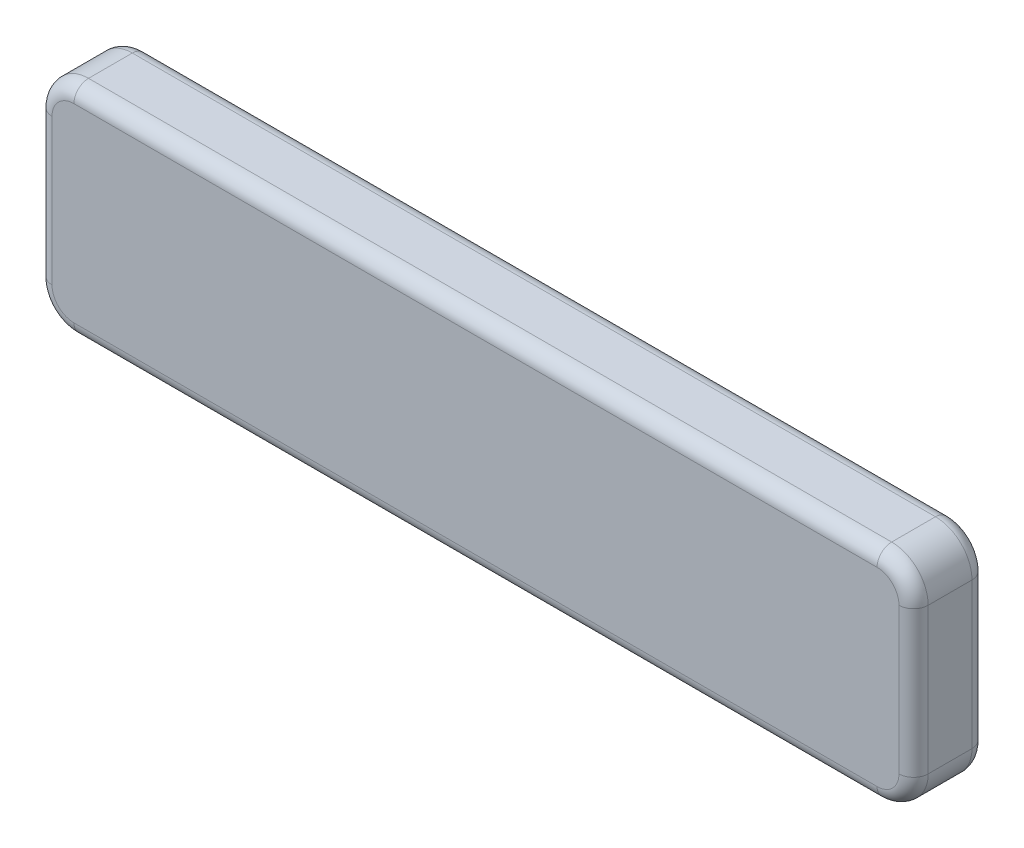
SolidWorks part; units mm, degrees
ref_plane "Front Plane" through (0, 0, 0) normal (0, 0, 1) x (1, 0, 0)
ref_plane "Top Plane" through (0, 0, 0) normal (0, 1, 0) x (1, 0, 0)
ref_plane "Right Plane" through (0, 0, 0) normal (1, 0, 0) x (0, 0, -1)
sketch "Sketch1" plane through (0, 0, 0) normal (0, 0, 1) x (1, 0, 0)
  line L1 (60, -15) -> (-60, -15)
  line L2 (60, -15) -> (60, 15)
  line L3 (60, 15) -> (-60, 15)
  line L4 (-60, -15) -> (-60, 15)
  line L5 (60, -15) -> (-60, 15) construction
  line L6 (60, 15) -> (-60, -15) construction
  point P0 (0, 0)
  dimension "D1" = 120
  dimension "D2" = 30
extrude "Boss-Extrude1" add sketch "Sketch1" along normal blind 10
fillet "Fillet1" radius 5 4 edges at (-60, -15, 5) (60, -15, 5) (60, 15, 5) (-60, 15, 5)
fillet "Fillet2" radius 2 16 edges at (58.5355, -13.5355, 0) (60, 0, 0) (58.5355, 13.5355, 0) (0, 15, 0) (-58.5355, 13.5355, 0) (-60, 0, 0) (-58.5355, -13.5355, 0) (0, -15, 0) (-58.5355, 13.5355, 10) (0, 15, 10) (58.5355, 13.5355, 10) (60, 0, 10) (58.5355, -13.5355, 10) (0, -15, 10) (-58.5355, -13.5355, 10) (-60, 0, 10)
